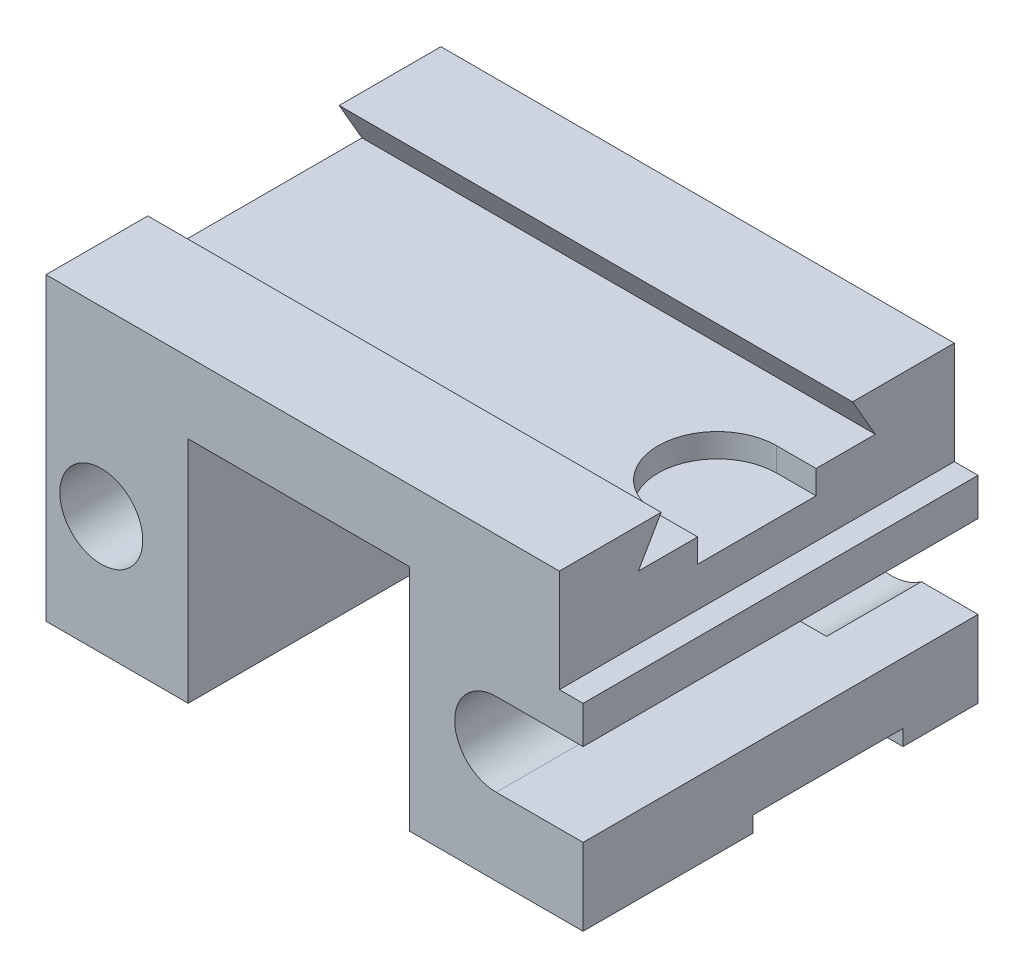
SolidWorks part; units mm, degrees
material "Polyetheretherketone (PEEK)"
ref_plane "Front Plane" through (0, 0, 0) normal (0, 0, 1) x (1, 0, 0)
ref_plane "Top Plane" through (0, 0, 0) normal (0, 1, 0) x (1, 0, 0)
ref_plane "Right Plane" through (0, 0, 0) normal (1, 0, 0) x (0, 0, -1)
ref_plane "Plane1" through (0, 4, 0) normal (0, 1, 0) x (-1, 0, 0)
sketch "Sketch1" plane through (0, 4, 0) normal (0, 1, 0) x (-1, 0, 0)
  line L0 (0, 0) -> (0, 5)
  line L1 (0, 5) -> (-6.8, 5)
  line L2 (-6.8, 5) -> (-6.8, 0)
  line L3 (-6.8, 0) -> (0, 0)
  dimension "D1" = 5
  dimension "D2" = 6.8
extrude "Boss-Extrude1" add sketch "Sketch1" against normal blind 3.8
sketch "Sketch3" plane through (0, 0, 5) normal (0, 0, 1) x (1, 0, 0)
  line L0 (1.8, 0.2) -> (4.6, 0.2)
  line L1 (4.6, 0.2) -> (4.6, 3.1)
  line L2 (4.6, 3.1) -> (1.8, 3.1)
  line L3 (1.8, 3.1) -> (1.8, 0.2)
  line L4 (0, 0.2) -> (6.8, 0.2) construction
  dimension "D1" = 2.8
  dimension "D2" = 2.9
extrude "Cut-Extrude2" cut sketch "Sketch3" against normal through all
sketch "Sketch4" plane through (6.8, 0, 0) normal (1, 0, 0) x (0, 0, -1)
  line L0 (-2.85, 0.2) -> (-0.95, 0.2)
  line L1 (-0.95, 0.2) -> (-0.95, 0.4)
  line L2 (-0.95, 0.4) -> (-2.85, 0.4)
  line L3 (-2.85, 0.4) -> (-2.85, 0.2)
  line L4 (-5, 0.2) -> (0, 0.2) construction
  dimension "D1" = 0.2
extrude "Cut-Extrude3" cut sketch "Sketch4" against normal blind 2.2
hole_wizard "Hole1" positions "Sketch7" profile "Sketch6" legacy end condition through all
sketch "Sketch7" plane through (0, 0, 0) normal (0, 0, -1) x (-1, 0, 0)
  point P0 (-5.7, 1.7)
  point P1 (-0.7, 1.7)
  dimension "D1" = 5
  dimension "D2" = 1.5
  dimension "D3" = 0.7
  dimension "D4" = 5.7
sketch "Sketch6" plane through (5.7, 1.7, 0) normal (1, 0, 0) x (0, 1, 0)
  line L0 (0, 0) -> (0, 5)
  line L1 (0, 5) -> (0.525, 5)
  line L2 (0.525, 5) -> (0.525, 1.2)
  line L3 (0.525, 1.2) -> (0.65, 1.2)
  line L4 (0.65, 1.2) -> (0.65, 0)
  line L5 (0.65, 0) -> (0, 0)
  line L6 (0, 110) -> (0, -10) construction
  dimension "Diameter" = 1.05
  dimension "Depth" = 5
  dimension "C-Bore Diameter" = 1.3
  dimension "C-Bore Depth" = 1.2
sketch "Sketch17" plane through (0, 0, 5) normal (0, 0, 1) x (1, 0, 0)
  line L0 (6.8, 4) -> (6.8, 0.2) construction
  line L2 (4.6, 0.2) -> (6.8, 0.2) construction
  line L4 (5.7, 2.225) -> (6.8, 2.225)
  line L5 (5.7, 2.225) -> (5.7, 1.175)
  line L6 (5.7, 1.175) -> (6.8, 1.175)
  line L7 (6.8, 2.225) -> (6.8, 1.175)
  circle A0 centre (5.7, 1.7) radius 0.525
  circle M1 centre (5.7, 1.7) radius 0.525
  line M12 (6.8, 0.2) -> (6.8, 4)
  dimension "D1" = 1.05
  dimension "D2" = 1.1
  dimension "D3" = 1.5
extrude "Cut-Extrude8" cut sketch "Sketch17" against normal through all contours L6 L4 M1 M12 | L5 M1 | L5 M1
sketch "Sketch18" plane through (6.8, 0, 0) normal (1, 0, 0) x (0, 0, -1)
  line L0 (-3.7113, 4) -> (-4, 3.5)
  line L1 (-5, 4) -> (-5, 2.225) construction
  line L2 (-5, 4) -> (0, 4) construction
  line L3 (-4, 3.5) -> (-1, 3.5)
  line L4 (-1, 3.5) -> (-1.2887, 4)
  line L8 (-1.2887, 4) -> (-3.7113, 4)
  line M8 (0, 4) -> (-5, 4)
  dimension "D1" = 3
  dimension "D2" = 60
  dimension "D3" = 60
  dimension "D4" = 1
  dimension "D5" = 0.5
extrude "Cut-Extrude9" cut sketch "Sketch18" against normal through all contours L3 L4 L0 M8
sketch "Sketch19" plane through (0, 3.5, 0) normal (0, 1, 0) x (1, 0, 0)
  line L0 (6.8, -4) -> (6.8, -1) construction
  line L1 (6, -1.75) -> (6.8, -1.75)
  line L2 (6, -1.75) -> (6, -3.25)
  line L3 (6, -3.25) -> (6.8, -3.25)
  line L4 (6.8, -1.75) -> (6.8, -3.25)
  line L5 (6.8, 0) -> (0, 0) construction
  circle A0 centre (6, -2.5) radius 0.75
  line M1 (6.8, -4) -> (6.8, -1)
  dimension "D1" = 1.5
  dimension "D2" = 2.5
  dimension "D3" = 6
extrude "Cut-Extrude10" cut sketch "Sketch19" against normal blind 0.3 contours L2 A0 L3 | L3 A0 L2 | A0 L3 L1 M1
sketch "Sketch20" plane through (6.8, 0, 0) normal (1, 0, 0) x (0, 0, -1)
  line L0 (0, 2.225) -> (0, 4) construction
  line L1 (-5, 4) -> (0, 4)
  line L2 (-5, 4) -> (-5, 2.7)
  line L3 (-5, 2.7) -> (0, 2.7)
  line L4 (0, 4) -> (0, 2.7)
  dimension "D1" = 1.3
extrude "Cut-Extrude11" cut sketch "Sketch20" against normal blind 0.3
sketch "Sketch22" plane through (0, 0, 0) normal (0, 0, -1) x (-1, 0, 0)
  line L0 (-6.8, 0.2) -> (-4.6, 0.2) construction
  line L1 (-6.8, 0.2) -> (-6.8, 1.175) construction
  line L3 (-5.6, 2.35) -> (-6.8, 2.35)
  line L4 (-5.6, 2.35) -> (-5.6, 1.05)
  line L5 (-5.6, 1.05) -> (-6.8, 1.05)
  line L6 (-6.8, 2.35) -> (-6.8, 1.05)
  circle A0 centre (-5.6, 1.7) radius 0.65
  line M2 (-6.8, 2.7) -> (-6.8, 2.225)
  line M3 (-6.8, 2.225) -> (-6.0832, 2.225)
  arc M4 (-6.0832, 2.225) -> (-6.0832, 1.175) centre (-5.7, 1.7) cw
  line M5 (-6.0832, 1.175) -> (-6.8, 1.175)
  line M6 (-6.8, 1.175) -> (-6.8, 0.2)
  dimension "D1" = 1.3
  dimension "D2" = 1.5
  dimension "D3" = 1.2
extrude "Cut-Extrude12" [suppressed] cut sketch "Sketch22" against normal blind 1.2 contours A0 L6 M4 M3 M5 | A0 L4 M4 | L4 M4 | L4 A0 M4 | L3 M4 M2 M3 | L5 M4 M5 M6 | A0 L4 M4 | A0 L5 M4 | A0 L3 M4 | L4 A0 M4
